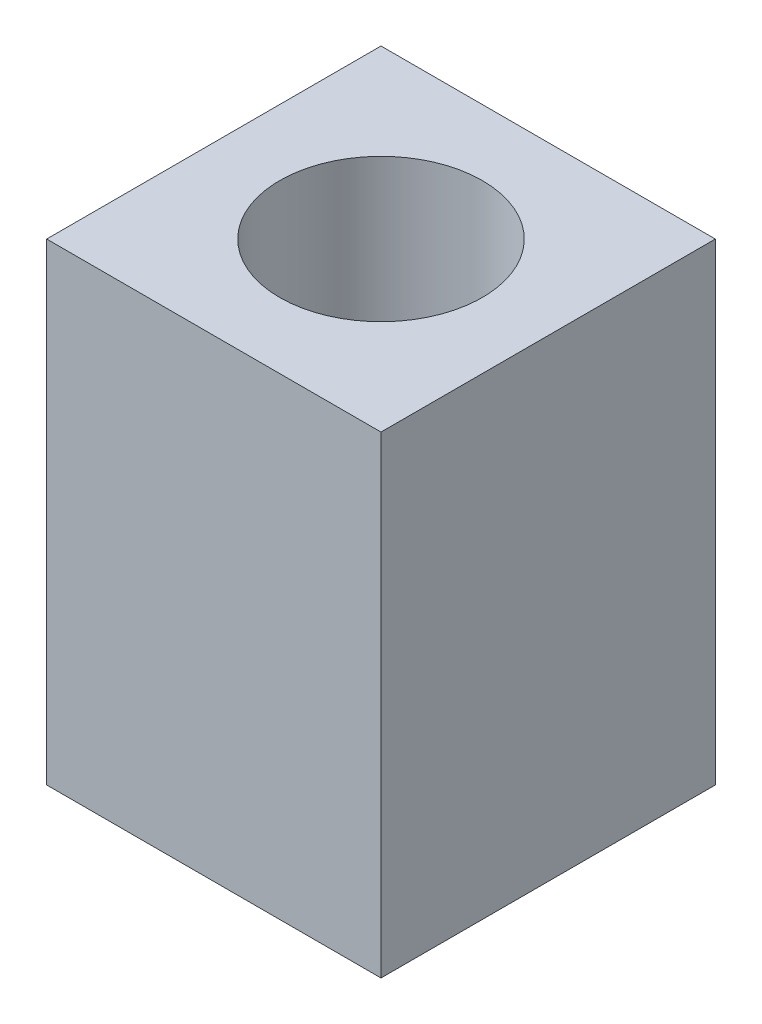
SolidWorks part; units mm, degrees
ref_plane "Front Plane" through (0, 0, 0) normal (0, 0, 1) x (1, 0, 0)
ref_plane "Top Plane" through (0, 0, 0) normal (0, 1, 0) x (1, 0, 0)
ref_plane "Right Plane" through (0, 0, 0) normal (1, 0, 0) x (0, 0, -1)
sketch "Sketch1" plane through (0, 0, 0) normal (0, 1, 0) x (1, 0, 0)
  line L0 (-4.9497, 4.9497) -> (0, 0) construction
  line L1 (0, 0) -> (-4.9497, 0)
  line L2 (0, 0) -> (0, 4.9497)
  line L3 (0, 4.9497) -> (-4.9497, 4.9497)
  line L4 (-4.9497, 0) -> (-4.9497, 4.9497)
  circle A0 centre (-2.4749, 2.4749) radius 1.5
  dimension "D2" = 3
  dimension "D1" = 7
extrude "Boss-Extrude1" add sketch "Sketch1" along normal blind 7
